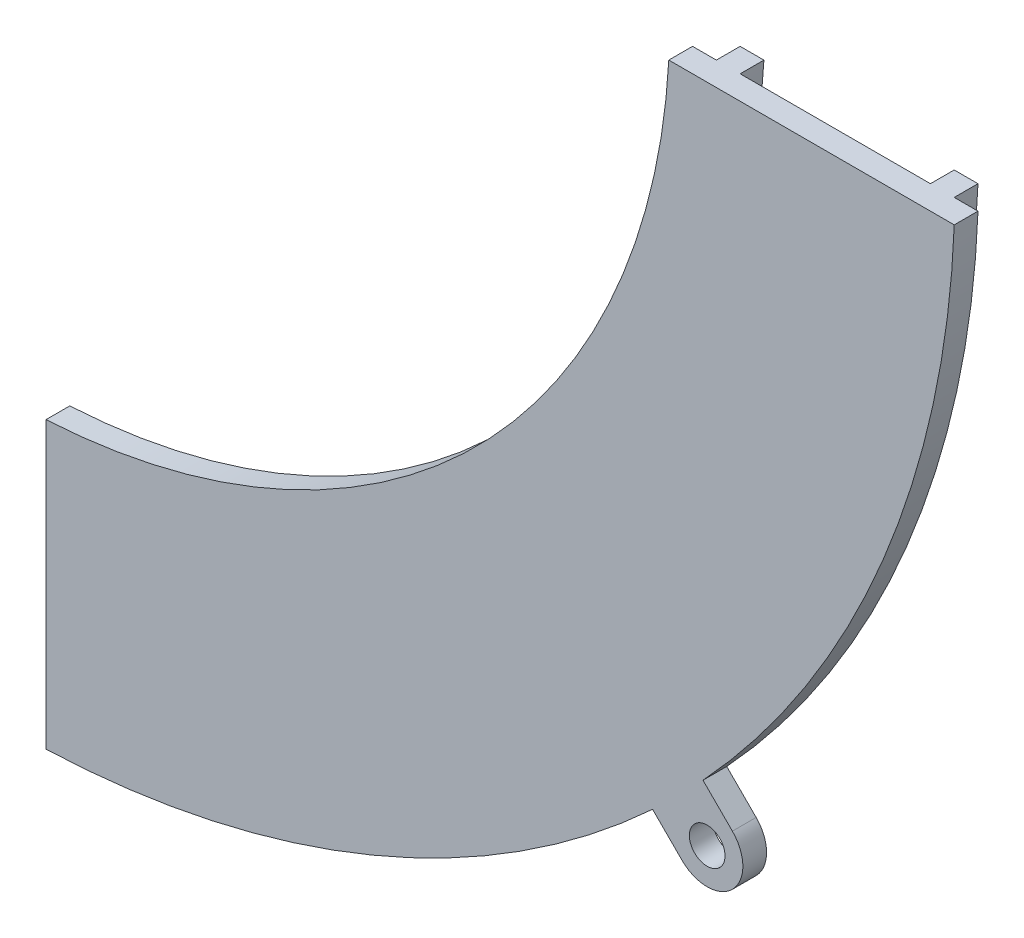
SolidWorks part; units mm, degrees
ref_plane "前视基准面" through (0, 0, 0) normal (0, 0, 1) x (1, 0, 0)
ref_plane "上视基准面" through (0, 0, 0) normal (0, 1, 0) x (1, 0, 0)
ref_plane "右视基准面" through (0, 0, 0) normal (1, 0, 0) x (0, 0, -1)
other "Configuration Table"
sketch "草图2" plane through (0, 0, 0) normal (0, 0, 1) x (1, 0, 0)
  line L0 (0, 0) -> (0, -67067.5378) construction
  line L1 (26.9546, 0) -> (-67067.5378, 0) construction
  line L2 (3, 0) -> (3, -3)
  line L3 (0, -3) -> (3, -3)
  line L4 (3, -77.4419) -> (3, -79.4434)
  line L5 (77.4419, -3) -> (79.4434, -3)
  line L6 (3, -55.4189) -> (3, -77.4419)
  line L7 (55.4189, -3) -> (77.4419, -3)
  arc A2 (3, -55.4189) -> (55.4189, -3) centre (0, 0) ccw
  arc A3 (3, -79.4434) -> (79.4434, -3) centre (0, 0) ccw
  dimension "D5" = 111
  dimension "D6" = 159
  dimension "D3" = 3
  dimension "D4" = 3
extrude "凸台-拉伸1" add sketch "草图2" along normal blind 2 contours L4 A3 L5 L7 A2 L6
sketch "草图3" plane through (0, 0, 0) normal (0, 0, 1) x (1, 0, 0)
  line L0 (3, -57.4217) -> (3, -59.4243)
  line L1 (3, -55.4189) -> (3, -79.4434) construction
  line L2 (77.4419, -3) -> (75.4404, -3)
  line L3 (55.4189, -3) -> (79.4434, -3) construction
  line L4 (59.4243, -3) -> (57.4217, -3)
  line L5 (3, -75.4404) -> (3, -77.4419)
  arc A0 (3, -57.4217) -> (57.4217, -3) centre (0, 0) ccw
  arc A1 (3, -77.4419) -> (77.4419, -3) centre (0, 0) ccw
  arc A2 (3, -59.4243) -> (59.4243, -3) centre (0, 0) ccw
  arc A3 (3, -75.4404) -> (75.4404, -3) centre (0, 0) ccw
  dimension "D1" = 115
  dimension "D2" = 155
  dimension "D3" = 119
  dimension "D4" = 151
extrude "凸台-拉伸2" add sketch "草图3" against normal blind 2
sketch "草图4" plane through (0, 0, 2) normal (0, 0, 1) x (1, 0, 0)
  line L0 (0, 0) -> (0, -50000) construction
  line L1 (0, 0) -> (-50000, 0) construction
  line L2 (0, 0) -> (35355.3391, -35355.3391) construction
  line L3 (54.0536, -58.2963) -> (66.111, -70.3536)
  line L4 (54.0536, -58.2963) -> (58.2963, -54.0536)
  line L5 (58.2963, -54.0536) -> (60.7711, -56.5285)
  arc A0 (3, -79.4434) -> (79.4434, -3) centre (0, 0) ccw construction
  arc A1 (60.7711, -56.5285) -> (56.5285, -60.7711) centre (58.6498, -58.6498) cw
  circle A2 centre (58.6498, -58.6498) radius 1.5
  arc M6 (3, -79.4434) -> (79.4434, -3) centre (0, 0) ccw
  dimension "D1" = 3
  dimension "D2" = 3
  dimension "D3" = 3.5
extrude "凸台-拉伸3" add sketch "草图4" against normal blind 2 contours A1 L5 L3 A2 M6
